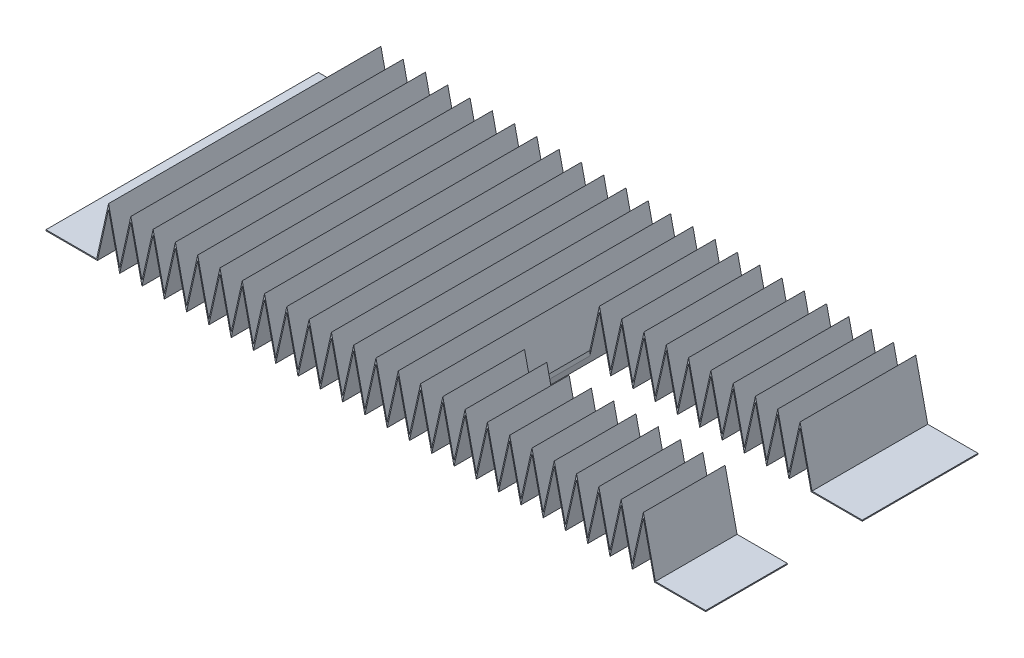
SolidWorks part; units mm, degrees
ref_plane "Front Plane" through (0, 0, 0) normal (0, 0, 1) x (1, 0, 0)
ref_plane "Top Plane" through (0, 0, 0) normal (0, 1, 0) x (1, 0, 0)
ref_plane "Right Plane" through (0, 0, 0) normal (1, 0, 0) x (0, 0, -1)
sketch "Sketch1" plane through (0, 0, 0) normal (0, 0, 1) x (1, 0, 0)
  line L0 (0, 0) -> (3.273, 14.741)
  line L1 (3.273, 14.741) -> (6.546, 0)
  line L2 (0, 0) -> (511, 0) construction
  line L3 (6.546, 0) -> (9.819, 14.741)
  line L4 (9.819, 14.741) -> (13.092, 0)
  line L5 (13.092, 0) -> (16.365, 14.741)
  line L6 (16.365, 14.741) -> (19.638, 0)
  line L7 (19.638, 0) -> (22.911, 14.741)
  line L8 (22.911, 14.741) -> (26.184, 0)
  line L9 (26.184, 0) -> (29.457, 14.741)
  line L10 (29.457, 14.741) -> (32.73, 0)
  line L11 (32.73, 0) -> (36.003, 14.741)
  line L12 (36.003, 14.741) -> (39.276, 0)
  line L13 (39.276, 0) -> (42.549, 14.741)
  line L14 (42.549, 14.741) -> (45.822, 0)
  line L15 (45.822, 0) -> (49.095, 14.741)
  line L16 (49.095, 14.741) -> (52.368, 0)
  line L17 (52.368, 0) -> (55.641, 14.741)
  line L18 (55.641, 14.741) -> (58.914, 0)
  line L19 (0, 0) -> (-15.1, 0)
  line L20 (58.914, 0) -> (62.187, 14.741)
  line L21 (62.187, 14.741) -> (65.46, 0)
  line L22 (65.46, 0) -> (68.733, 14.741)
  line L23 (68.733, 14.741) -> (72.006, 0)
  line L24 (72.006, 0) -> (75.279, 14.741)
  line L25 (75.279, 14.741) -> (78.552, 0)
  line L26 (78.552, 0) -> (81.825, 14.741)
  line L27 (81.825, 14.741) -> (85.098, 0)
  line L28 (85.098, 0) -> (88.371, 14.741)
  line L29 (88.371, 14.741) -> (91.644, 0)
  line L30 (91.644, 0) -> (94.917, 14.741)
  line L31 (94.917, 14.741) -> (98.19, 0)
  line L32 (98.19, 0) -> (101.463, 14.741)
  line L33 (101.463, 14.741) -> (104.736, 0)
  line L34 (104.736, 0) -> (108.009, 14.741)
  line L35 (108.009, 14.741) -> (111.282, 0)
  line L36 (111.282, 0) -> (114.555, 14.741)
  line L37 (114.555, 14.741) -> (117.828, 0)
  line L38 (80.65, -119) -> (80.65, 132.963) construction
  line L39 (117.828, 0) -> (121.101, 14.741)
  line L40 (121.101, 14.741) -> (124.374, 0)
  line L41 (124.374, 0) -> (127.647, 14.741)
  line L42 (127.647, 14.741) -> (130.92, 0)
  line L43 (130.92, 0) -> (134.193, 14.741)
  line L44 (134.193, 14.741) -> (137.466, 0)
  line L45 (137.466, 0) -> (140.739, 14.741)
  line L46 (140.739, 14.741) -> (144.012, 0)
  line L47 (144.012, 0) -> (147.285, 14.741)
  line L48 (147.285, 14.741) -> (150.558, 0)
  line L49 (150.558, 0) -> (153.831, 14.741)
  line L51 (153.831, 14.741) -> (157.104, 0)
  line L52 (157.104, 0) -> (160.377, 14.741)
  line L53 (160.377, 14.741) -> (163.65, 0)
  line L54 (163.65, 0) -> (178.65, 0)
  dimension "D1" = 511
  dimension "D2" = 15.1
  dimension "D3" = 15
  dimension "D4" = 6.546
  dimension "D6" = 98
  dimension "D5" = 25
extrude "Extrude-Thin1" add sketch "Sketch1" along normal mid plane 80 thin thin type one direction reverse wall 0.3
sketch "Sketch2" plane through (0, 0, 0) normal (0, 1, 0) x (1, 0, 0)
  line L1 (98.65, -16) -> (178.65, -16)
  line L2 (98.65, -16) -> (98.65, 6)
  line L3 (98.65, 6) -> (178.65, 6)
  line L4 (178.65, -16) -> (178.65, 6)
  line L5 (98.65, -16) -> (178.65, 6) construction
  line L6 (98.65, 6) -> (178.65, -16) construction
  line L8 (178.65, -40) -> (178.65, 40) construction
  point P0 (138.65, -5)
  dimension "D1" = 80
  dimension "D2" = 22
  dimension "D3" = 5
extrude "Cut-Extrude4" cut sketch "Sketch2" against normal through all and the other way through all contours L1 L4 L3 L2
